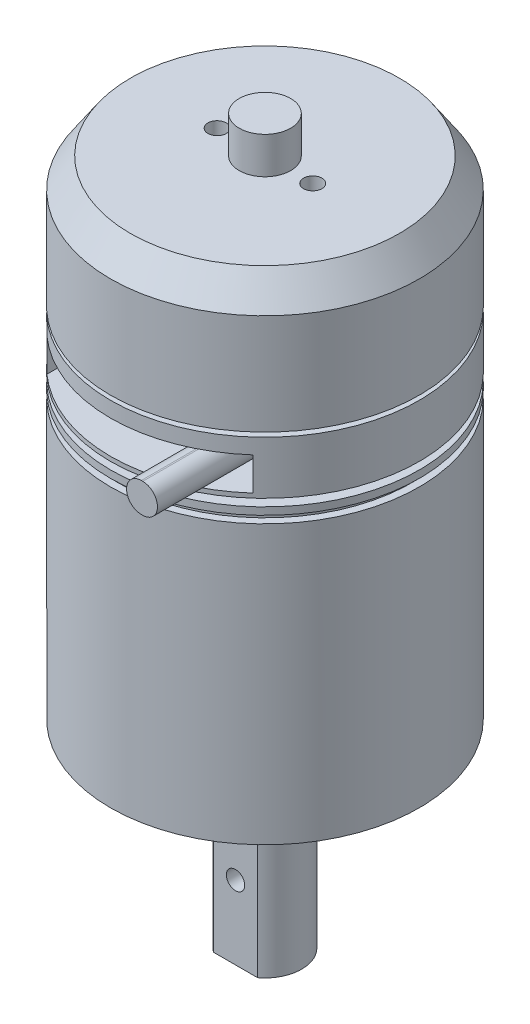
SolidWorks part; units mm, degrees
ref_plane "前视基准面" through (0, 0, 0) normal (0, 0, 1) x (1, 0, 0)
ref_plane "上视基准面" through (0, 0, 0) normal (0, 1, 0) x (1, 0, 0)
ref_plane "右视基准面" through (0, 0, 0) normal (1, 0, 0) x (0, 0, -1)
sketch "草图1" plane through (0, 0, 0) normal (0, 0, 1) x (1, 0, 0)
  line L0 (0, 0) -> (4.1, 0)
  line L1 (4.1, 0) -> (4.1, 6.7)
  line L2 (4.1, 6.7) -> (13.4, 6.7)
  line L3 (13.4, 6.7) -> (13.4, 8.7)
  line L4 (13.4, 8.7) -> (21, 8.7)
  line L5 (21, 8.7) -> (21, 10.2)
  line L6 (21, 10.2) -> (20, 10.2)
  line L7 (20, 10.2) -> (20, 11.2)
  line L8 (20, 11.2) -> (21, 11.2)
  line L9 (21, 11.2) -> (21, 12.2)
  line L10 (21, 12.2) -> (10, 12.2)
  line L11 (10, 12.2) -> (10, 13.2)
  line L12 (10, 13.2) -> (21, 13.2)
  line L13 (21, 13.2) -> (21, 20.4)
  line L14 (21, 20.4) -> (5, 20.4)
  line L15 (5, 20.4) -> (5, 21)
  line L16 (5, 21) -> (21, 21)
  line L17 (21, 21) -> (21, 34.7)
  line L18 (21, 34.7) -> (18.3, 38.7)
  line L19 (18.3, 38.7) -> (3.5, 38.7)
  line L20 (3.5, 38.7) -> (3.5, 43.7)
  line L21 (3.5, 43.7) -> (0, 43.7)
  line L22 (0, 43.7) -> (0, 0) construction
  line L23 (0, 0) -> (0, 43.7)
  dimension "D1" = 8.2
  dimension "D2" = 26.8
  dimension "D3" = 42
  dimension "D4" = 10
  dimension "D5" = 1.5
  dimension "D6" = 1
  dimension "D7" = 1
  dimension "D8" = 20
  dimension "D9" = 1
  dimension "D10" = 7.2
  dimension "D11" = 0.6
  dimension "D12" = 13.7
  dimension "D13" = 5
  dimension "D14" = 2
  dimension "D15" = 6.7
  dimension "D16" = 1
  dimension "D17" = 7
  dimension "D18" = 36.6
  dimension "D19" = 4
  dimension "D20" = 30
revolve "旋转1" add sketch "草图1" angle 360 about L22
ref_plane "基准面1" through (0, 0, 21) normal (0, 0, 1) x (1, 0, 0)
sketch "草图2" plane through (0, 0, 21) normal (0, 0, 1) x (1, 0, 0)
  line L1 (-14, 18.3) -> (14, 18.3)
  line L2 (-14, 18.3) -> (-14, 13.8)
  line L3 (-14, 13.8) -> (14, 13.8)
  line L4 (14, 18.3) -> (14, 13.8)
  line L5 (-14, 18.3) -> (14, 13.8) construction
  line L6 (-14, 13.8) -> (14, 18.3) construction
  line L7 (-21, 13.2) -> (21, 13.2) construction
  point P0 (0, 16.05)
  dimension "D1" = 28
  dimension "D2" = 4.5
  dimension "D3" = 0.6
extrude "切除-拉伸1" cut sketch "草图2" against normal blind 10
sketch "草图3" plane through (0, 0, 11) normal (0, 0, 1) x (1, 0, 0)
  line L0 (9.1851, 16.0532) -> (9.3851, 16.0532) construction
  line L1 (9.1851, 18.0532) -> (9.3851, 18.0532)
  line L2 (9.1851, 14.0532) -> (9.3851, 14.0532)
  arc A0 (9.1851, 18.0532) -> (9.1851, 14.0532) centre (9.1851, 16.0532) ccw
  arc A1 (9.3851, 14.0532) -> (9.3851, 18.0532) centre (9.3851, 16.0532) ccw
  point P2 (9.2851, 16.0532)
  dimension "D1" = 4
  dimension "D2" = 0.2
extrude "凸台-拉伸1" add sketch "草图3" along normal blind 15
hole_wizard "M3 螺纹孔1" positions "草图5" profile "草图6" tap size "M3" standard "GB"
sketch "草图5" plane through (0, 38.7, 0) normal (0, 1, 0) x (1, 0, 0)
  line L0 (0, 0) -> (0, 8.0606) construction
  point P0 (-6.5, 0)
  point P2 (6.5, 0)
  dimension "D1" = 13
sketch "草图6" plane through (-6.5, 38.7, 0) normal (1, 0, 0) x (0, 0, 1)
  line L0 (0, 0) -> (0, 4.7511)
  line L1 (0, 4.7511) -> (1.25, 4)
  line L2 (1.25, 4) -> (1.25, 0)
  line L5 (1.25, 0) -> (0, 0)
  line L10 (0, 4.7511) -> (-1.25, 4) construction
  line L11 (0, -6.35) -> (0, 107.95) construction
  dimension "螺纹孔钻头直径" = 2.5
  dimension "螺纹孔钻头深度" = 4
  dimension "导头角度" = 118
cosmetic thread "孔螺蚊线1" parameters "D1"=4, "D2"=3
cosmetic thread "孔螺蚊线2" parameters "D1"=4, "D2"=3
sketch "草图7" plane through (0, 0, 0) normal (0, 0, 1) x (1, 0, 0)
  line L0 (0, 8.7) -> (0, -54.6) construction
  line L1 (-13.4, 8.7) -> (13.4, 8.7) construction
  line L2 (0, -54.6) -> (5, -54.6)
  line L3 (5, -54.6) -> (5, -30.5)
  line L4 (5, -30.5) -> (8.275, -30.5)
  line L5 (13, -29.6) -> (13, -27.6)
  line L6 (13, -27.6) -> (21, -27.6)
  line L7 (21, -27.6) -> (21, 8.7)
  line L8 (-21, 8.7) -> (21, 8.7) construction
  line L9 (21, 8.7) -> (0, 8.7)
  line L10 (18.3, 38.7) -> (-18.3, 38.7) construction
  line L11 (13, -29.6) -> (8.275, -29.6)
  line L12 (8.275, -29.6) -> (8.275, -30.5)
  line L13 (0, 8.7) -> (0, -54.6)
  dimension "D1" = 66.3
  dimension "D2" = 2
  dimension "D3" = 0.9
  dimension "D4" = 27
  dimension "D5" = 26
  dimension "D6" = 10
  dimension "D7" = 16.55
revolve "旋转2" add sketch "草图7" angle 360 about L0
sketch "草图8" plane through (0, -54.6, 0) normal (0, -1, 0) x (1, 0, 0)
  line L0 (-3, 4) -> (3, 4)
  circle A0 centre (0, 0) radius 5 construction
  circle A1 centre (0, 0) radius 5 construction
  arc A2 (3, 4) -> (-3, 4) centre (0, 0) ccw
  dimension "D1" = 4
extrude "切除-拉伸2" cut sketch "草图8" against normal blind 20
hole_wizard "M4 螺纹孔1" positions "草图10" profile "草图9" tap size "M4" standard "GB"
sketch "草图10" plane through (0, -27.6, 0) normal (0, -1, 0) x (-1, 0, 0)
  circle A0 centre (0, 0) radius 17.5
  point P5 (0, -17.5)
  point P7 (-17.5, 0)
  point P9 (0, 17.5)
  point P11 (17.5, 0)
  dimension "D1" = 35
sketch "草图9" plane through (0, -27.6, 17.5) normal (1, 0, 0) x (0, 0, -1)
  line L0 (0, 0) -> (0, 11.0914)
  line L1 (0, 11.0914) -> (1.65, 10.1)
  line L2 (1.65, 10.1) -> (1.65, 0)
  line L5 (1.65, 0) -> (0, 0)
  line L10 (0, 11.0914) -> (-1.65, 10.1) construction
  line L11 (0, -6.35) -> (0, 107.95) construction
  dimension "螺纹孔钻头直径" = 3.3
  dimension "螺纹孔钻头深度" = 10.1
  dimension "导头角度" = 118
cosmetic thread "孔螺蚊线3" parameters "D1"=8, "D2"=4
cosmetic thread "孔螺蚊线4" parameters "D1"=8, "D2"=4
cosmetic thread "孔螺蚊线5" parameters "D1"=8, "D2"=4
cosmetic thread "孔螺蚊线6" parameters "D1"=8, "D2"=4
sketch "草图11" plane through (0, 0, 4) normal (0, 0, 1) x (1, 0, 0)
  line L0 (0, -54.6) -> (0, -36.079) construction
  line L1 (-3, -54.6) -> (3, -54.6) construction
  line L2 (-13.929, -44.6) -> (10.5915, -44.6) construction
  circle A0 centre (0, -44.6) radius 1.9071
  dimension "D1" = 10
hole_wizard "M3 螺纹孔2" positions "3D草图1" profile "草图12" tap size "M3" standard "GB" end condition through all
sketch3d "3D草图1"
  point P0 (0, -44.6, 4)
sketch "草图12" plane through (0, -44.6, 4) normal (1, 0, 0) x (0, -1, 0)
  line L0 (0, 0) -> (0, 25)
  line L1 (0, 25) -> (1.25, 25)
  line L2 (1.25, 25) -> (1.25, 0)
  line L5 (1.25, 0) -> (0, 0)
  line L11 (0, -6.35) -> (0, 107.95) construction
  dimension "螺纹线主直径" = 2.5
  dimension "通孔螺纹孔钻头深度" = 25
